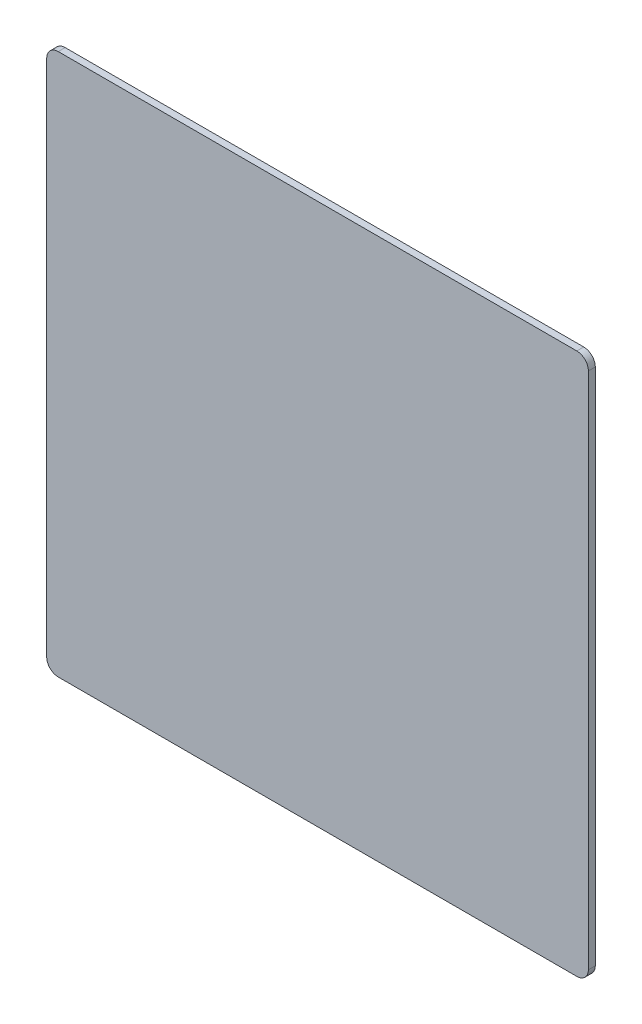
SolidWorks part; units mm, degrees
ref_plane "Plan de face" through (0, 0, 0) normal (0, 0, 1) x (1, 0, 0)
ref_plane "Plan de dessus" through (0, 0, 0) normal (0, 1, 0) x (1, 0, 0)
ref_plane "Plan de droite" through (0, 0, 0) normal (1, 0, 0) x (0, 0, -1)
sketch "Esquisse1" plane through (0, 0, 0) normal (0, 0, 1) x (1, 0, 0)
  line L0 (-117.5, 112.5) -> (-117.5, -112.5) construction
  line L1 (112.5, 117.5) -> (-112.5, 117.5) construction
  line L2 (-112.5, -117.5) -> (112.5, -117.5) construction
  line L3 (117.5, -112.5) -> (117.5, 112.5) construction
  line L4 (-117.5, 112.5) -> (-117.5, -112.5)
  line L5 (112.5, 117.5) -> (-112.5, 117.5)
  line L6 (-112.5, -117.5) -> (112.5, -117.5)
  line L7 (117.5, -112.5) -> (117.5, 112.5)
  arc A0 (-112.5, 117.5) -> (-117.5, 112.5) centre (-112.5, 112.5) ccw construction
  arc A1 (-117.5, -112.5) -> (-112.5, -117.5) centre (-112.5, -112.5) ccw construction
  arc A2 (117.5, 112.5) -> (112.5, 117.5) centre (112.5, 112.5) ccw construction
  arc A3 (112.5, -117.5) -> (117.5, -112.5) centre (112.5, -112.5) ccw construction
  arc A4 (-112.5, 117.5) -> (-117.5, 112.5) centre (-112.5, 112.5) ccw
  arc A5 (-117.5, -112.5) -> (-112.5, -117.5) centre (-112.5, -112.5) ccw
  arc A6 (117.5, 112.5) -> (112.5, 117.5) centre (112.5, 112.5) ccw
  arc A7 (112.5, -117.5) -> (117.5, -112.5) centre (112.5, -112.5) ccw
extrude "Boss.-Extru.1" add sketch "Esquisse1" along normal blind 3
